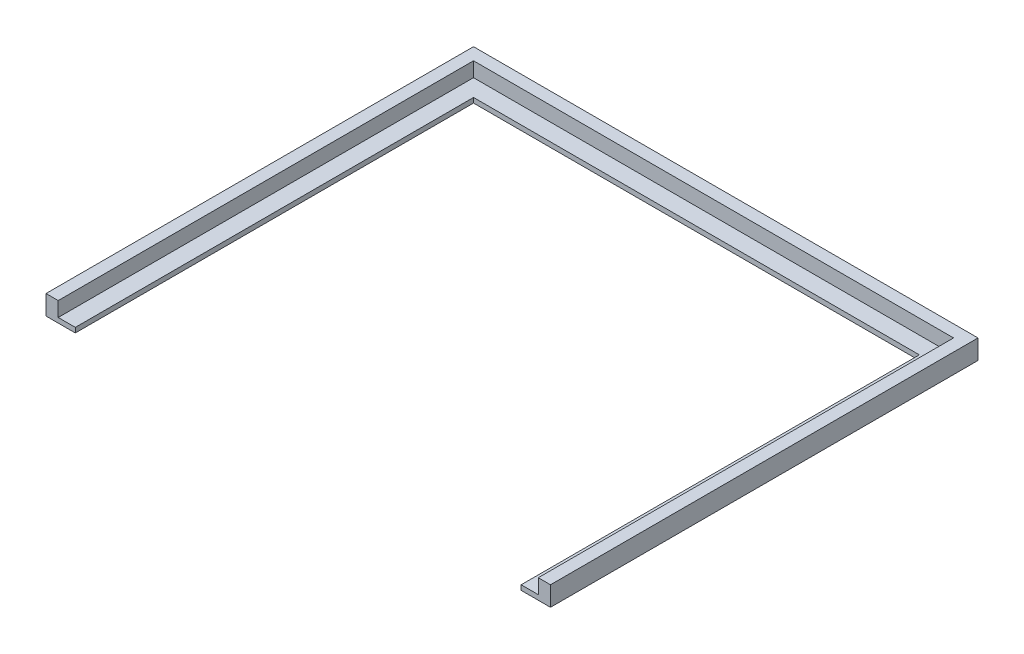
SolidWorks part; units mm, degrees
ref_plane "Front Plane" through (0, 0, 0) normal (0, 0, 1) x (1, 0, 0)
ref_plane "Top Plane" through (0, 0, 0) normal (0, 1, 0) x (1, 0, 0)
ref_plane "Right Plane" through (0, 0, 0) normal (1, 0, 0) x (0, 0, -1)
sketch "Sketch1" plane through (0, 0, 0) normal (0, 1, 0) x (1, 0, 0)
  line L0 (-91.25, 163) -> (-91.25, 175) construction
  line L1 (103.25, -175) -> (-103.25, -175)
  line L2 (103.25, -175) -> (103.25, 175)
  line L3 (103.25, 175) -> (-103.25, 175)
  line L4 (-103.25, -175) -> (-103.25, 175)
  line L5 (103.25, -175) -> (-103.25, 175) construction
  line L6 (103.25, 175) -> (-103.25, -175) construction
  line L7 (91.25, -163) -> (-91.25, -163)
  line L8 (91.25, -163) -> (91.25, 163)
  line L9 (91.25, 163) -> (-91.25, 163)
  line L10 (-91.25, -163) -> (-91.25, 163)
  line L11 (91.25, -163) -> (-91.25, 163) construction
  line L12 (91.25, 163) -> (-91.25, -163) construction
  line L13 (-91.25, 163) -> (-103.25, 163) construction
  point P0 (0, 0)
  point P6 (0, 0)
  dimension "D1" = 350
  dimension "D2" = 12
  dimension "D3" = 206.5
extrude "Boss-Extrude1" add sketch "Sketch1" along normal blind 2
sketch "Sketch2" plane through (0, 2, 0) normal (0, 1, 0) x (1, 0, 0)
  line L0 (-98.25, 170) -> (-98.25, -170)
  line L1 (-98.25, -170) -> (98.25, -170)
  line L2 (98.25, -170) -> (98.25, 170)
  line L3 (98.25, 170) -> (-98.25, 170)
  line L4 (-103.25, 175) -> (-103.25, -175)
  line L5 (-103.25, -175) -> (103.25, -175)
  line L6 (103.25, -175) -> (103.25, 175)
  line L7 (103.25, 175) -> (-103.25, 175)
  line L8 (-103.25, 175) -> (-103.25, -175)
  line L9 (-103.25, -175) -> (103.25, -175)
  line L10 (103.25, -175) -> (103.25, 175)
  line L11 (103.25, 175) -> (-103.25, 175)
  dimension "D1" = 0
  dimension "D2" = 5
extrude "Boss-Extrude2" add sketch "Sketch2" along normal blind 6
sketch "Sketch3" plane through (0, 0, 0) normal (0, 1, 0) x (1, 0, 0)
  line L1 (-200, 0) -> (200, 0)
  line L2 (-200, 0) -> (-200, -400)
  line L3 (-200, -400) -> (200, -400)
  line L4 (200, 0) -> (200, -400)
  point P4 (-350.2088, -454.1501)
  point P6 (-141.6017, 0)
  point P7 (0, 0)
  dimension "D1" = 400
  dimension "D2" = 400
extrude "Cut-Extrude3" cut sketch "Sketch3" against normal through all and the other way through all
